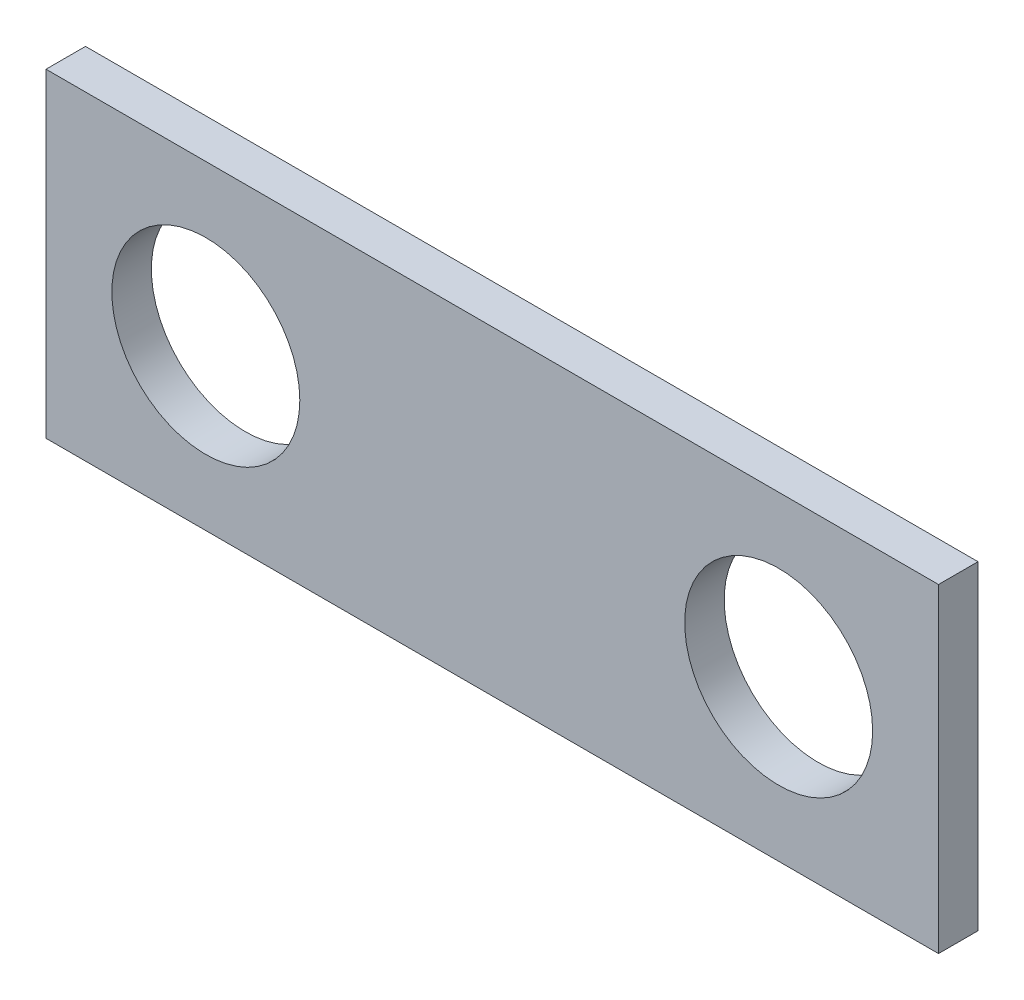
SolidWorks part; units mm, degrees
ref_plane "Front Plane" through (0, 0, 0) normal (0, 0, 1) x (1, 0, 0)
ref_plane "Top Plane" through (0, 0, 0) normal (0, 1, 0) x (1, 0, 0)
ref_plane "Right Plane" through (0, 0, 0) normal (1, 0, 0) x (0, 0, -1)
sketch "Sketch1" plane through (0, 0, 0) normal (0, 0, 1) x (1, 0, 0)
  line L0 (10, 48.5496) -> (10, 0) construction
  line L1 (0, 0) -> (135.5496, 0)
  line L2 (0, 0) -> (0, 48.5496)
  line L3 (0, 48.5496) -> (135.5496, 48.5496)
  line L4 (135.5496, 0) -> (135.5496, 48.5496)
  line L5 (125.5496, 48.5496) -> (125.5496, 0) construction
  line L6 (0, 10) -> (135.5496, 10) construction
  line L7 (0, 38.5496) -> (135.5496, 38.5496) construction
  circle A0 centre (24.2748, 24.2748) radius 14.2748
  circle A1 centre (111.2748, 24.2748) radius 14.2748
  dimension "D5" = 28.5496
  dimension "D1" = 10
  dimension "D2" = 10
  dimension "D3" = 10
  dimension "D4" = 10
  dimension "D6" = 87
extrude "Boss-Extrude1" add sketch "Sketch1" along normal blind 6
